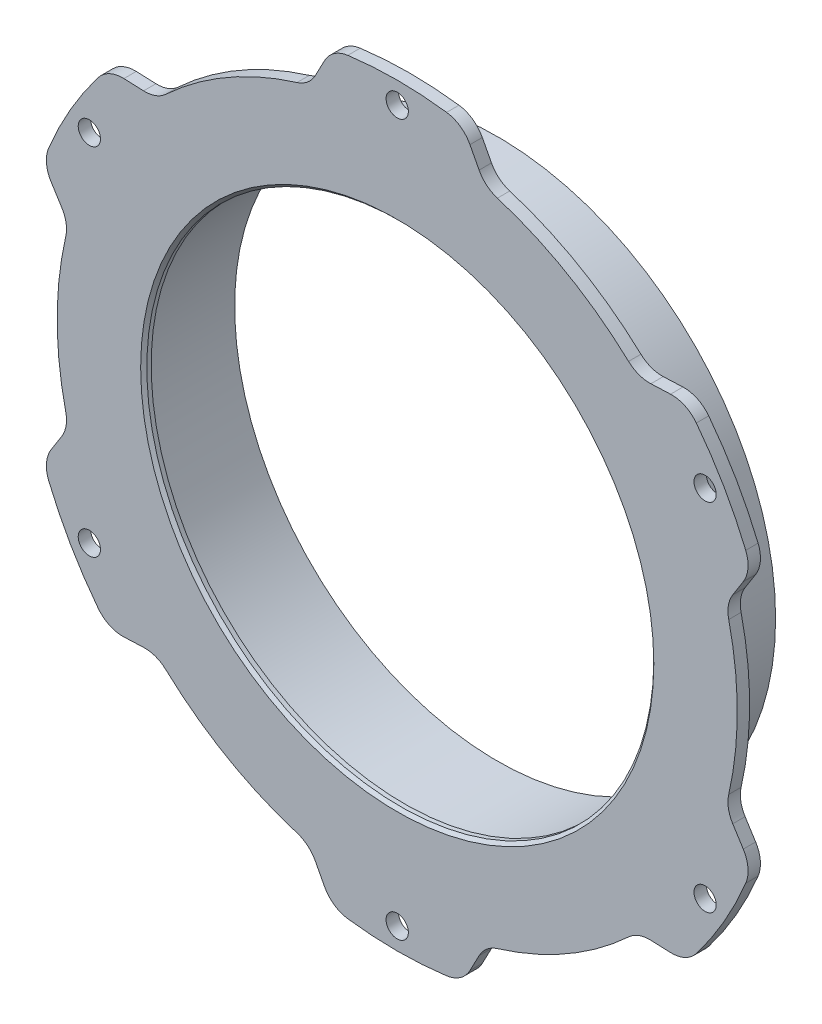
SolidWorks part; units mm, degrees
ref_plane "Front Plane" through (0, 0, 0) normal (0, 0, 1) x (1, 0, 0)
ref_plane "Top Plane" through (0, 0, 0) normal (0, 1, 0) x (1, 0, 0)
ref_plane "Right Plane" through (0, 0, 0) normal (1, 0, 0) x (0, 0, -1)
sketch "Sketch3" plane through (0, 0, 0) normal (1, 0, 0) x (0, 0, -1)
  line L8 (0, 77.47) -> (0, 52.705)
  line L9 (0.635, 52.07) -> (1.524, 52.07)
  line L11 (1.524, 53.975) -> (20.574, 53.975)
  line L12 (20.574, 53.975) -> (20.574, 57.15)
  line L15 (2.54, 77.47) -> (0, 77.47)
  line L16 (2.54, 77.47) -> (2.54, 63.5)
  line L17 (8.89, 57.15) -> (20.574, 57.15)
  line L18 (0, 52.705) -> (0.635, 52.07)
  line L19 (0, 0) -> (21.539, 0) construction
  line L20 (1.524, 53.975) -> (1.524, 52.07)
  arc A0 (2.54, 63.5) -> (8.89, 57.15) centre (8.89, 63.5) ccw
  point P1 (0, 52.07)
  dimension "D7" = 6.35
  dimension "D1" = 52.07
  dimension "D2" = 1.524
  dimension "D3" = 19.05
  dimension "D4" = 53.975
  dimension "D5" = 57.15
  dimension "D6" = 77.47
  dimension "D8" = 2.54
revolve "Revolve1" add sketch "Sketch3" angle 360 about L19
sketch "Sketch4" plane through (0, 0, 0) normal (0, 0, 1) x (1, 0, 0)
  line L0 (0, 0) -> (0, 77.47) construction
  line L1 (0, 0) -> (13.4525, 76.2931) construction
  line L2 (0, 0) -> (18.0785, 67.4699) construction
  line L3 (0, 0) -> (38.735, 67.091) construction
  line L4 (14.9401, 73.4558) -> (16.8195, 69.8713)
  line L5 (-14.9401, 73.4558) -> (-16.8195, 69.8713)
  line L6 (56.1445, 49.6664) -> (52.1005, 49.5017)
  line L7 (71.0846, 23.7894) -> (68.92, 20.3695)
  line L8 (71.0846, -23.7894) -> (68.92, -20.3695)
  line L9 (56.1445, -49.6664) -> (52.1005, -49.5017)
  line L10 (14.9401, -73.4558) -> (16.8195, -69.8713)
  line L11 (-14.9401, -73.4558) -> (-16.8195, -69.8713)
  line L12 (-56.1445, -49.6664) -> (-52.1005, -49.5017)
  line L13 (-71.0846, -23.7894) -> (-68.92, -20.3695)
  line L14 (-71.0846, 23.7894) -> (-68.92, 20.3695)
  line L15 (-56.1445, 49.6664) -> (-52.1005, 49.5017)
  circle A0 centre (0, 0) radius 69.85 construction
  circle A1 centre (0, 0) radius 77.47 construction
  circle A2 centre (0, 0) radius 77.47
  arc A3 (10.148, 76.8025) -> (-10.148, 76.8025) centre (0, 0) ccw
  arc A4 (14.9401, 73.4558) -> (10.148, 76.8025) centre (9.3162, 70.5072) ccw
  arc A5 (20.5731, 66.7516) -> (34.925, 60.4919) centre (0, 0) cw
  arc A6 (-20.5731, 66.7516) -> (-34.925, 60.4919) centre (0, 0) ccw
  arc A7 (-14.9401, 73.4558) -> (-10.148, 76.8025) centre (-9.3162, 70.5072) cw
  arc A8 (47.522, 51.1926) -> (34.925, 60.4919) centre (0, 0) ccw
  arc A9 (56.1445, 49.6664) -> (61.4389, 47.1897) centre (56.4029, 43.3217) cw
  arc A10 (71.5869, 29.6128) -> (61.4389, 47.1897) centre (0, 0) ccw
  arc A11 (71.0846, 23.7894) -> (71.5869, 29.6128) centre (65.7191, 27.1855) ccw
  arc A12 (68.0951, 15.559) -> (69.85, 0) centre (0, 0) cw
  arc A13 (68.0951, -15.559) -> (69.85, 0) centre (0, 0) ccw
  arc A14 (71.0846, -23.7894) -> (71.5869, -29.6128) centre (65.7191, -27.1855) cw
  arc A15 (61.4389, -47.1897) -> (71.5869, -29.6128) centre (0, 0) ccw
  arc A16 (56.1445, -49.6664) -> (61.4389, -47.1897) centre (56.4029, -43.3217) ccw
  arc A17 (47.522, -51.1926) -> (34.925, -60.4919) centre (0, 0) cw
  arc A18 (20.5731, -66.7516) -> (34.925, -60.4919) centre (0, 0) ccw
  arc A19 (14.9401, -73.4558) -> (10.148, -76.8025) centre (9.3162, -70.5072) cw
  arc A20 (-10.148, -76.8025) -> (10.148, -76.8025) centre (0, 0) ccw
  arc A21 (-14.9401, -73.4558) -> (-10.148, -76.8025) centre (-9.3162, -70.5072) ccw
  arc A22 (-20.5731, -66.7516) -> (-34.925, -60.4919) centre (0, 0) cw
  arc A23 (-47.522, -51.1926) -> (-34.925, -60.4919) centre (0, 0) ccw
  arc A24 (-56.1445, -49.6664) -> (-61.4389, -47.1897) centre (-56.4029, -43.3217) cw
  arc A25 (-71.5869, -29.6128) -> (-61.4389, -47.1897) centre (0, 0) ccw
  arc A26 (-71.0846, -23.7894) -> (-71.5869, -29.6128) centre (-65.7191, -27.1855) ccw
  arc A27 (-68.0951, -15.559) -> (-69.85, 0) centre (0, 0) cw
  arc A28 (-68.0951, 15.559) -> (-69.85, 0) centre (0, 0) ccw
  arc A29 (-71.0846, 23.7894) -> (-71.5869, 29.6128) centre (-65.7191, 27.1855) cw
  arc A30 (-61.4389, 47.1897) -> (-71.5869, 29.6128) centre (0, 0) ccw
  arc A31 (-56.1445, 49.6664) -> (-61.4389, 47.1897) centre (-56.4029, 43.3217) ccw
  arc A32 (-47.522, 51.1926) -> (-34.925, 60.4919) centre (0, 0) cw
  circle A33 centre (0, 73.025) radius 2.286
  circle A34 centre (63.2415, 36.5125) radius 2.286
  circle A35 centre (63.2415, -36.5125) radius 2.286
  circle A36 centre (0, -73.025) radius 2.286
  circle A37 centre (-63.2415, -36.5125) radius 2.286
  circle A38 centre (-63.2415, 36.5125) radius 2.286
  arc A39 (-20.5731, 66.7516) -> (-16.8195, 69.8713) centre (-22.4434, 72.8199) ccw
  arc A40 (-52.1005, 49.5017) -> (-47.522, 51.1926) centre (-51.8422, 55.8465) ccw
  arc A41 (-68.0951, 15.559) -> (-68.92, 20.3695) centre (-74.2856, 16.9734) ccw
  arc A42 (-68.92, -20.3695) -> (-68.0951, -15.559) centre (-74.2856, -16.9734) ccw
  arc A43 (-47.522, -51.1926) -> (-52.1005, -49.5017) centre (-51.8422, -55.8465) ccw
  arc A44 (-16.8195, -69.8713) -> (-20.5731, -66.7516) centre (-22.4434, -72.8199) ccw
  arc A45 (20.5731, -66.7516) -> (16.8195, -69.8713) centre (22.4434, -72.8199) ccw
  arc A46 (52.1005, -49.5017) -> (47.522, -51.1926) centre (51.8422, -55.8465) ccw
  arc A47 (68.0951, -15.559) -> (68.92, -20.3695) centre (74.2856, -16.9734) ccw
  arc A48 (68.92, 20.3695) -> (68.0951, 15.559) centre (74.2856, 16.9734) ccw
  arc A49 (47.522, 51.1926) -> (52.1005, 49.5017) centre (51.8422, 55.8465) ccw
  arc A50 (16.8195, 69.8713) -> (20.5731, 66.7516) centre (22.4434, 72.8199) ccw
  point P69 (0, 0)
  point P71 (75.5425, 46.4805)
  point P72 (0, 0)
  point P82 (0, 0)
  point P86 (-18.0785, 67.4699)
  circle M9 centre (0, 0) radius 77.47
  dimension "D1" = 139.7
  dimension "D5" = 6.35
  dimension "D7" = 4.572
  dimension "D10" = 6.35
  dimension "D2" = 30
  dimension "D3" = 15
  dimension "D4" = 10
  dimension "D8" = 73.025
  dimension "D6" = 6
  dimension "D9" = 6
extrude "Cut-Extrude1" cut sketch "Sketch4" against normal through all contours L15 A32 A6 L5 A7 A2 A31 | L6 A9 A4 L4 A5 A8 M9 | L8 A14 A11 L7 A12 A13 M9 | L10 A19 A16 L9 A17 A18 M9 | L12 A24 A21 L11 A22 A23 M9 | L14 A29 A26 L13 A27 A28 M9 | A33 | A34 | A35 | A36 | A37 | A38
